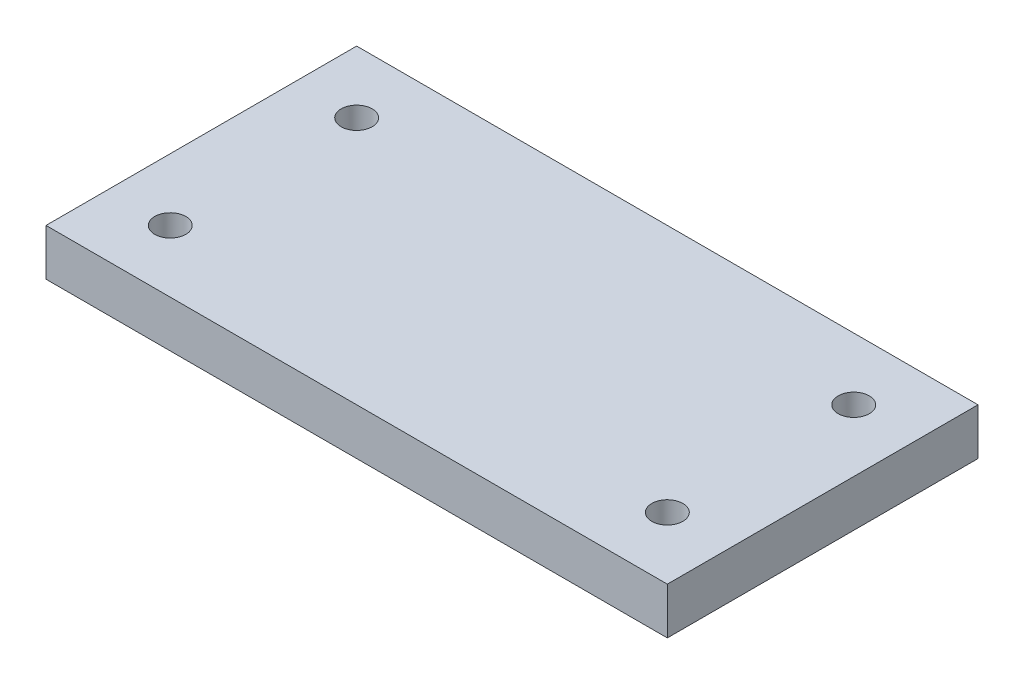
SolidWorks part; units mm, degrees
ref_plane "前视基准面" through (0, 0, 0) normal (0, 0, 1) x (1, 0, 0)
ref_plane "上视基准面" through (0, 0, 0) normal (0, 1, 0) x (1, 0, 0)
ref_plane "右视基准面" through (0, 0, 0) normal (1, 0, 0) x (0, 0, -1)
other "Configuration Table"
sketch "草图1" plane through (0, 0, 0) normal (0, 1, 0) x (1, 0, 0)
  line L1 (-100, -50) -> (100, -50)
  line L2 (-100, -50) -> (-100, 50)
  line L3 (-100, 50) -> (100, 50)
  line L4 (100, -50) -> (100, 50)
  line L5 (-100, -50) -> (100, 50) construction
  line L6 (-100, 50) -> (100, -50) construction
extrude "凸台-拉伸1" add sketch "草图1" along normal blind 15
sketch "草图2" plane through (0, 0, 0) normal (0, 1, 0) x (1, 0, 0)
  circle A0 centre (-80, -30) radius 5
  circle A1 centre (80, -30) radius 5
  circle A2 centre (-80, 30) radius 5
extrude "切除-拉伸1" cut sketch "草图2" along normal blind 30
sketch "草图3" plane through (0, 0, 0) normal (0, 1, 0) x (1, 0, 0)
  circle A0 centre (80, 30) radius 5
extrude "切除-拉伸2" cut sketch "草图3" along normal blind 30
